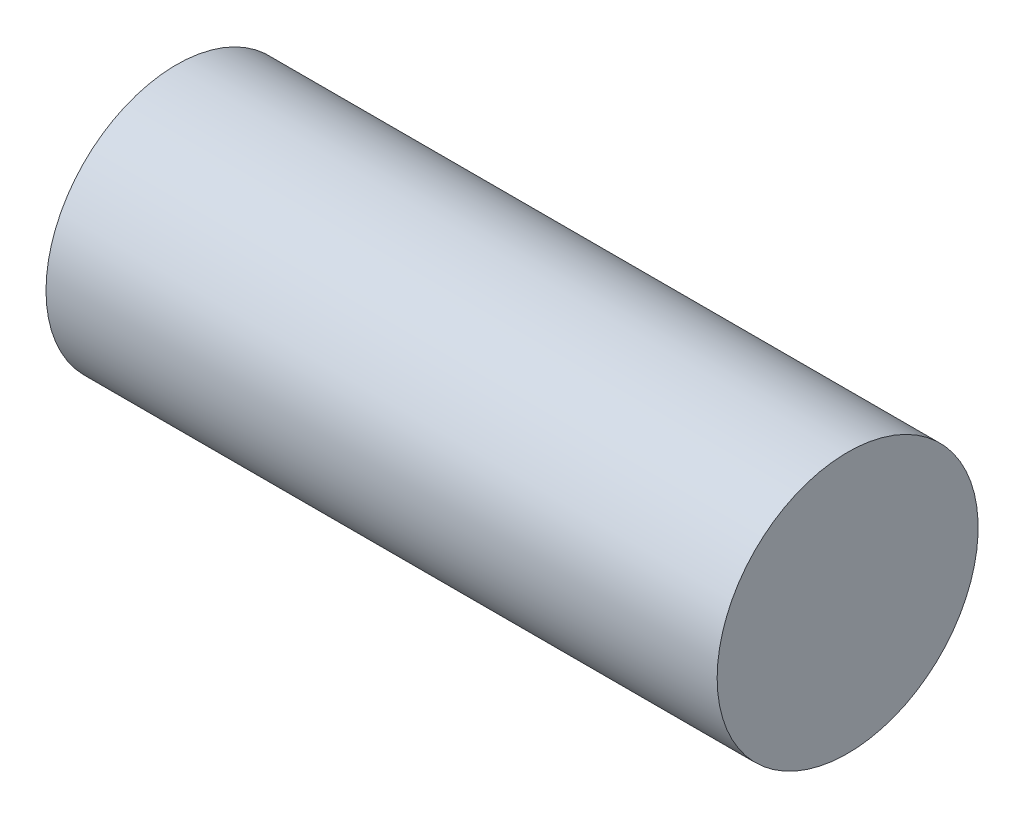
SolidWorks part; units mm, degrees
material "Nylon 101"
ref_plane "Front Plane" through (0, 0, 0) normal (0, 0, 1) x (1, 0, 0)
ref_plane "Top Plane" through (0, 0, 0) normal (0, 1, 0) x (1, 0, 0)
ref_plane "Right Plane" through (0, 0, 0) normal (1, 0, 0) x (0, 0, -1)
sketch "Sketch1" plane through (0, 0, 0) normal (1, 0, 0) x (0, 0, -1)
  circle A0 centre (0, 0) radius 35
  dimension "D1" = 70
extrude "Boss-Extrude1" add sketch "Sketch1" along normal mid plane 180
sketch "Sketch2" plane through (-90, 0, 0) normal (-1, 0, 0) x (0, 0, 1)
  point P0 (0, 0)
ref_point "Point2"
